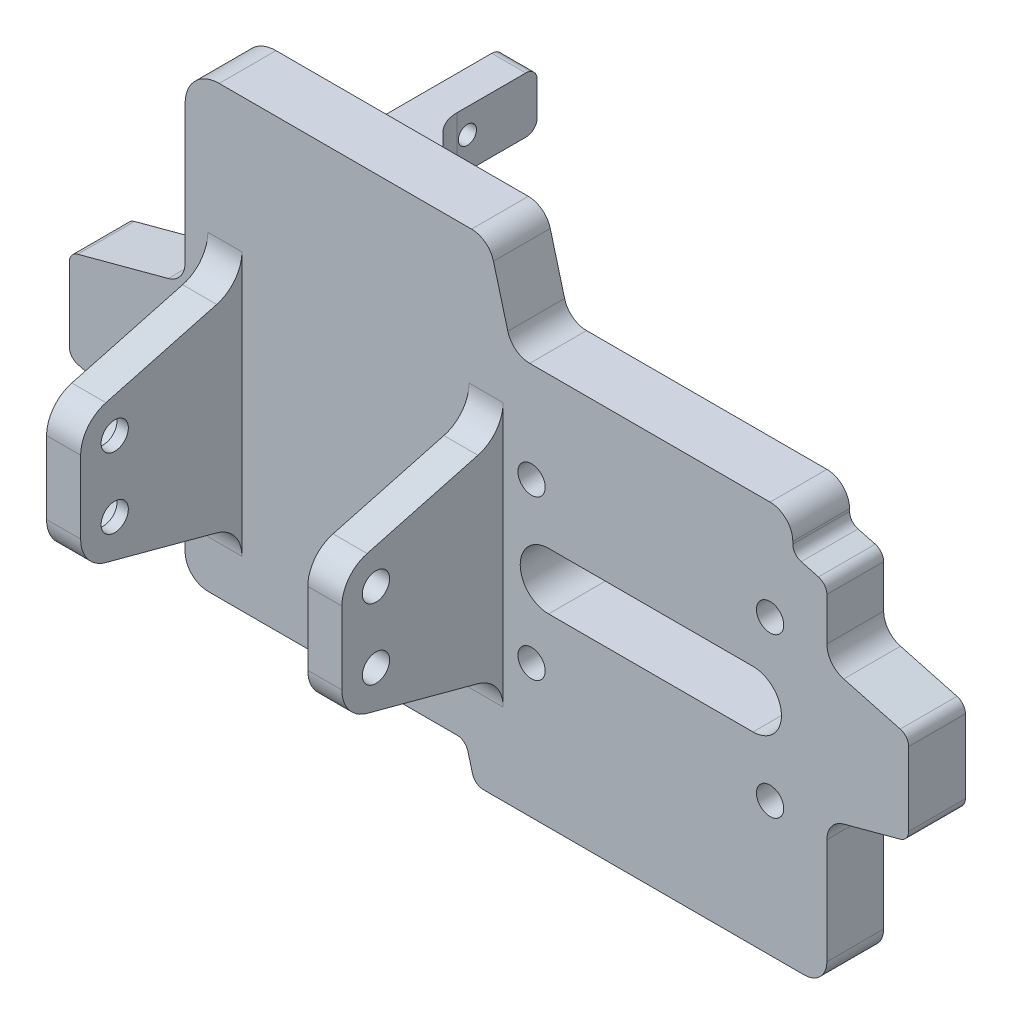
SolidWorks part; units mm, degrees
material "ABS"
ref_plane "Front Plane" through (0, 0, 0) normal (0, 0, 1) x (1, 0, 0)
ref_plane "Top Plane" through (0, 0, 0) normal (0, 1, 0) x (1, 0, 0)
ref_plane "Right Plane" through (0, 0, 0) normal (1, 0, 0) x (0, 0, -1)
sketch "Sketch1" plane through (0, 0, 0) normal (0, 0, 1) x (1, 0, 0)
  line L1 (-26.75, -15.775) -> (26.75, -15.775)
  line L2 (-26.75, -15.775) -> (-26.75, 15.775)
  line L3 (-26.75, 15.775) -> (26.75, 15.775)
  line L4 (26.75, -15.775) -> (26.75, 15.775)
  line L5 (-26.75, -15.775) -> (26.75, 15.775) construction
  line L6 (-26.75, 15.775) -> (26.75, -15.775) construction
  point P0 (0, 0)
  dimension "D1" = 53.5
  dimension "D2" = 31.55
extrude "Boss-Extrude1" add sketch "Sketch1" along normal mid plane 5
sketch "Sketch2" plane through (0, 0, 2.5) normal (0, 0, 1) x (1, 0, 0)
  line L0 (-18.55, 21.45) -> (-16.05, 21.45) construction
  line L1 (26.75, 15.775) -> (-26.75, 15.775) construction
  line L7 (-26.75, 15.775) -> (-26.75, 20.45)
  line L10 (-29.95, 0) -> (-26.75, 0) construction
  line L11 (-26.75, 15.775) -> (-26.75, -15.775) construction
  line L12 (-29.95, 0) -> (-36.95, 0) construction
  line L13 (-36.95, -4) -> (-36.95, 4)
  line L14 (-36.95, 4) -> (-26.75, 6.7331)
  line L15 (-36.95, -4) -> (-26.75, -6.7331)
  line L16 (-26.75, 6.7331) -> (-26.75, -6.7331)
  line L17 (0, 0) -> (0, -22.5323) construction
  line L22 (-2.0538, -15.775) -> (-1.25, -18.775)
  line L23 (-26.75, -15.775) -> (26.75, -15.775) construction
  line L24 (-1.25, -18.775) -> (29.75, -18.775)
  line L25 (29.75, -18.775) -> (29.75, 12)
  line L26 (29.75, 12) -> (26.75, 12.8038)
  line L27 (26.75, -15.775) -> (26.75, 15.775) construction
  line L28 (26.75, 12.8038) -> (26.75, -15.775)
  line L29 (26.75, -15.775) -> (-2.0538, -15.775)
  line L30 (36.95, -4) -> (36.95, 4)
  line L31 (36.95, 4) -> (29.75, 5.9292)
  line L32 (36.95, 0) -> (29.75, 0) construction
  line L33 (36.95, -4) -> (29.75, -5.9292)
  line L34 (-23.75, 23.45) -> (0, 23.45)
  line L35 (0, 23.45) -> (2.0565, 15.775)
  line L36 (-26.75, 15.775) -> (2.0565, 15.775)
  line L37 (24.75, 9) -> (3.75, 9) construction
  line L38 (1.75, -7) -> (1.75, -15) construction
  arc A0 (-26.75, 20.45) -> (-23.75, 23.45) centre (-23.75, 20.45) cw
  point P0 (-23.5391, 22.8262)
  dimension "D2" = 3
  dimension "D3" = 7
  dimension "D4" = 4
  dimension "D5" = 15
  dimension "D6" = 3
  dimension "D7" = 3
  dimension "D8" = 75
  dimension "D9" = 105
  dimension "D10" = 15
  dimension "D11" = 75
  dimension "D12" = 3
  dimension "D13" = 3
  dimension "D14" = 2
extrude "Boss-Extrude2" add sketch "Sketch2" against normal up to surface (5 mm away) up to face at (0, 0, -2.5)
fillet "Fillet1" radius 2 9 edges at (-26.75, -15.775, 0) (26.75, 15.775, 0) (-26.75, 6.7331, 0) (29.75, 5.9292, 0) (29.75, -18.775, 0) (29.75, -5.9292, 0) (-26.75, -6.7331, 0) (0, 23.45, 0) (2.0565, 15.775, 0)
fillet "Fillet2" radius 1 8 edges at (36.95, -4, 0) (36.95, 4, 0) (29.75, 12, 0) (26.75, 12.8038, 0) (-1.25, -18.775, 0) (-2.0538, -15.775, 0) (-36.95, 4, 0) (-36.95, -4, 0)
ref_plane "Plane1" through (-21.75, 0, 0) normal (-1, 0, 0) x (0, 0, 1)
sketch "Sketch3" plane through (-21.75, 0, 0) normal (-1, 0, 0) x (0, 0, 1)
  line L0 (2.5, 0) -> (16.7008, 0) construction
  line L1 (2.5, -3.2327) -> (2.5, 3.2327) construction
  line L2 (16.7008, -5.5) -> (16.7008, 5.5)
  line L3 (16.7008, 5.5) -> (2.5, 9.3051)
  line L4 (2.5, 20.45) -> (2.5, 8.2677) construction
  line L5 (2.5, 9.3051) -> (2.5, -9.3051)
  line L6 (16.7008, -5.5) -> (2.5, -9.3051)
  circle A0 centre (13.7008, 3) radius 1 construction
  circle A1 centre (13.7008, -3) radius 1 construction
  circle A2 centre (13.7008, 3) radius 1 construction
  circle A3 centre (13.7008, -3) radius 1 construction
  dimension "D1" = 15
  dimension "D2" = 2.5
  dimension "D3" = 3
extrude "Boss-Extrude3" add sketch "Sketch3" along normal blind 3 contours L2 L3 L5 L6
fillet "Fillet3" radius 3 4 edges at (-23.25, 5.5, 16.7008) (-23.25, -5.5, 16.7008) (-23.25, -9.3051, 2.5) (-23.25, 9.3051, 2.5)
ref_plane "Plane2" through (-11.75, 0, 0) normal (1, 0, 0) x (0, 0, -1)
mirror "Mirror1" about plane through (-11.75, 0, 0) normal (1, 0, 0) of "Fillet3", "Boss-Extrude3"
sketch "Sketch4" plane through (0, 0, -2.5) normal (0, 0, -1) x (-1, 0, 0)
  line L0 (16.05, 16.55) -> (16.05, 21.45) construction
  line L1 (16.05, 16.55) -> (16.05, 21.45) construction
  line L2 (0.25, 16.55) -> (16.05, 16.55) construction
  line L3 (16.05, 21.45) -> (13.05, 21.45)
  line L4 (16.05, 21.45) -> (16.05, 16.55)
  line L5 (16.05, 16.55) -> (13.05, 16.55)
  line L6 (13.05, 21.45) -> (13.05, 16.55)
  line L7 (16.05, -6.15) -> (16.05, -11.05) construction
  line L8 (16.05, -6.15) -> (16.05, -11.05) construction
  line L10 (16.05, -6.15) -> (13.05, -6.15)
  line L11 (16.05, -6.15) -> (16.05, -11.05)
  line L12 (16.05, -11.05) -> (13.05, -11.05)
  line L13 (13.05, -6.15) -> (13.05, -11.05)
  dimension "D1" = 3
  dimension "D2" = 3
extrude "Boss-Extrude4" add sketch "Sketch4" along normal up to surface (12.3 mm away)
chamfer "Chamfer1" distance 4 angle 45 2 edges at (-13.05, -8.6, -2.5) (-13.05, 19, -2.5)
fillet "Fillet4" radius 3 4 edges at (-9.05, 19, -2.5) (-13.05, 19, -6.5) (-9.05, -8.6, -2.5) (-13.05, -8.6, -6.5)
fillet "Fillet5" radius 1 4 edges at (-14.55, -11.05, -14.8) (-14.55, -6.15, -14.8) (-14.55, 16.55, -14.8) (-14.55, 21.45, -14.8)
hole_wizard "M2 Clearance Hole1" positions "Sketch5" profile "Sketch6" hole size "M2" standard "ANSI Metric" end condition through all
sketch "Sketch5" plane through (0, 0, 2.5) normal (0, 0, 1) x (1, 0, 0)
  point P0 (3.75, 7)
  point P3 (3.75, -7)
  point P6 (24.75, -7)
  point P9 (24.75, 7)
sketch "Sketch6" plane through (3.75, 7, 2.5) normal (1, 0, 0) x (0, -1, 0)
  line L0 (0, 0) -> (0, 17.3)
  line L1 (0, 17.3) -> (1.2, 17.3)
  line L2 (1.2, 17.3) -> (1.2, 0)
  line L5 (1.2, 0) -> (0, 0)
  line L11 (0, -6.35) -> (0, 107.95) construction
  dimension "Thru Hole Dia." = 2.4
  dimension "Thru Hole Depth" = 17.3
hole_wizard "M2x0.4 Tapped Hole1" positions "Sketch7" profile "Sketch8" tap size "M2x0.4" standard "ANSI Metric" end condition through all
sketch "Sketch7" plane through (-16.05, 0, 0) normal (-1, 0, 0) x (0, 0, 1)
  point P0 (-8.65, 19.3)
  point P2 (-8.65, -8.9)
sketch "Sketch8" plane through (-16.05, 19.3, -8.65) normal (0, 1, 0) x (0, 0, 1)
  line L0 (0, 0) -> (0, 53)
  line L1 (0, 53) -> (0.8, 53)
  line L2 (0.8, 53) -> (0.8, 0)
  line L5 (0.8, 0) -> (0, 0)
  line L11 (0, -6.35) -> (0, 107.95) construction
  dimension "Thru Tap Drill Dia." = 1.6
  dimension "Thru Tap Drill Depth" = 53
cosmetic thread "Hole Thread1" parameters "D2"=2
cosmetic thread "Hole Thread2" parameters "D2"=2
hole_wizard "CBORE for M2 SHCS1" positions "Sketch9" profile "Sketch10" counterbore size "M2" standard "ANSI Metric" end condition through all
sketch "Sketch9" plane through (-24.75, 0, 0) normal (-1, 0, 0) x (0, 0, 1)
  point P0 (13.7008, 3.198)
  point P3 (13.7008, -3)
sketch "Sketch10" plane through (-24.75, 3.198, 13.7008) normal (0, 1, 0) x (0, 0, 1)
  line L0 (0, 0) -> (0, 61.7)
  line L1 (0, 61.7) -> (1.2, 61.7)
  line L3 (1.2, 61.7) -> (1.2, 2)
  line L4 (1.2, 2) -> (2.2, 2)
  line L5 (2.2, 2) -> (2.2, 0)
  line L7 (2.2, 0) -> (0, 0)
  line L11 (0, -6.35) -> (0, 107.95) construction
  dimension "Thru Hole Dia." = 2.4
  dimension "Thru Hole Depth" = 61.7
  dimension "C'Bore Dia." = 4.4
  dimension "C'Bore Depth" = 2
sketch "Sketch13" plane through (0, 0, 2.5) normal (0, 0, 1) x (1, 0, 0)
  line L0 (5.25, 0) -> (23.25, 0) construction
  line L1 (5.25, 2.5) -> (23.25, 2.5)
  line L2 (5.25, -2.5) -> (23.25, -2.5)
  arc A0 (5.25, 2.5) -> (5.25, -2.5) centre (5.25, 0) ccw
  arc A1 (23.25, -2.5) -> (23.25, 2.5) centre (23.25, 0) ccw
  point P4 (14.25, 0)
  dimension "D1" = 2.5
extrude "Cut-Extrude1" cut sketch "Sketch13" against normal through all
